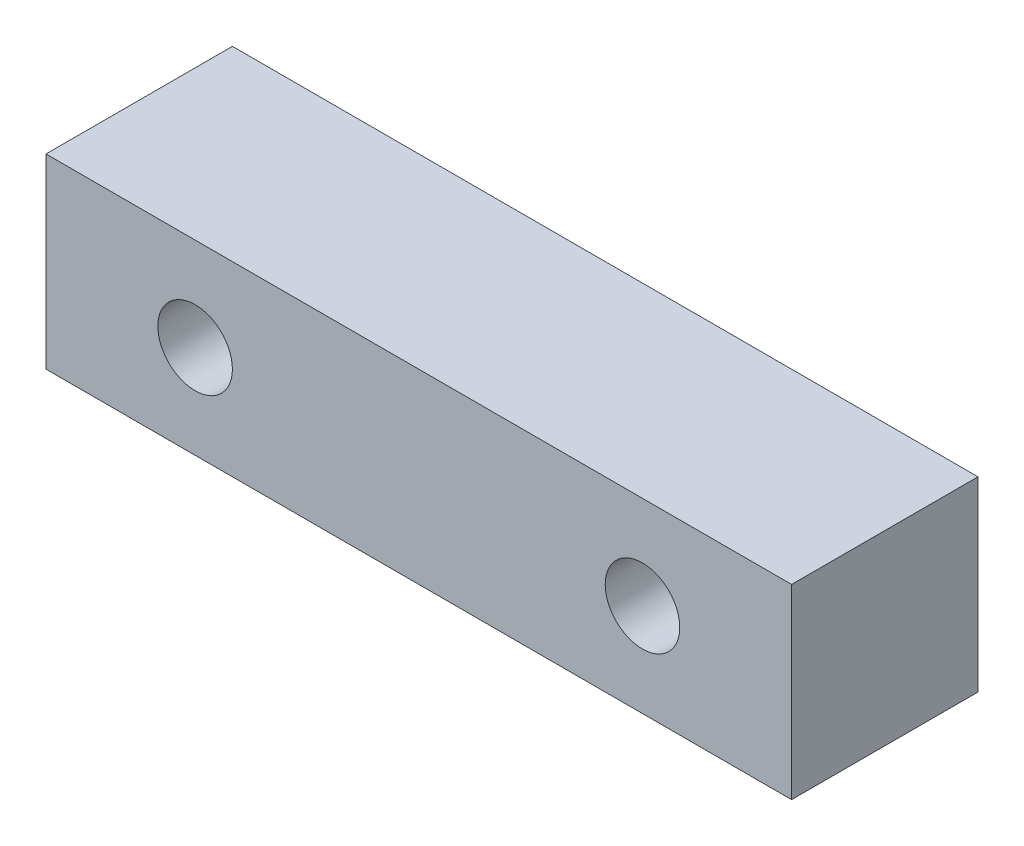
SolidWorks part; units mm, degrees
ref_plane "前视基准面" through (0, 0, 0) normal (0, 0, 1) x (1, 0, 0)
ref_plane "上视基准面" through (0, 0, 0) normal (0, 1, 0) x (1, 0, 0)
ref_plane "右视基准面" through (0, 0, 0) normal (1, 0, 0) x (0, 0, -1)
sketch "草图1" plane through (0, 0, 0) normal (0, 0, 1) x (1, 0, 0)
  line L0 (0, 5.5949) -> (0, 2.5) construction
  line L1 (10, 2.5) -> (10, -2.5)
  line L2 (-10, 2.5) -> (10, 2.5)
  line L3 (-10, 2.5) -> (-10, -2.5)
  line L6 (-10, -2.5) -> (10, -2.5)
  line L7 (-15.0023, 0) -> (18.5512, 0) construction
  circle A0 centre (-6, 0) radius 1
  circle A1 centre (6, 0) radius 1
  point P9 (10, 0)
  point P11 (-10, 0)
  dimension "D1" = 2
  dimension "D2" = 12
  dimension "D3" = 5
  dimension "D4" = 20
extrude "凸台-拉伸1" add sketch "草图1" along normal blind 5
